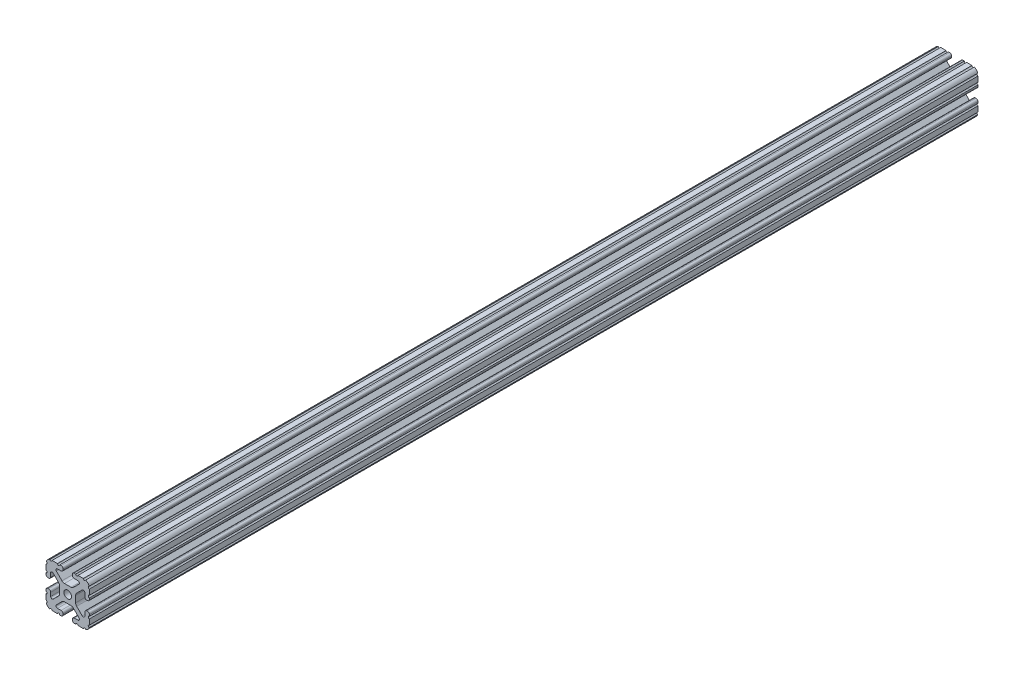
SolidWorks part; units mm, degrees
ref_plane "Front Plane" through (0, 0, 0) normal (0, 0, 1) x (1, 0, 0)
ref_plane "Top Plane" through (0, 0, 0) normal (0, 1, 0) x (1, 0, 0)
ref_plane "Right Plane" through (0, 0, 0) normal (1, 0, 0) x (0, 0, -1)
sketch "Sketch2" plane through (0, 0, 0) normal (0, 0, 1) x (1, 0, 0)
  line L0 (0, 19.05) -> (0, -19.05) construction
  line L1 (-19.05, 0) -> (19.05, 0) construction
  line L2 (4.064, -19.05) -> (19.05, -19.05)
  line L3 (19.05, -19.05) -> (19.05, -4.064)
  line L4 (4.064, -19.05) -> (4.064, -14.986)
  line L5 (4.064, -14.986) -> (12.1123, -14.986)
  line L6 (12.1123, -14.986) -> (4.1113, -6.985)
  line L7 (0, 0) -> (19.05, -19.05) construction
  line L8 (19.05, -4.064) -> (14.986, -4.064)
  line L9 (14.986, -4.064) -> (14.986, -12.1123)
  line L10 (14.986, -12.1123) -> (6.985, -4.1113)
  circle A0 centre (0, 0) radius 3.3274
  arc A1 (8.9963, -14.986) -> (9.909, -12.7826) centre (8.9963, -13.6953) ccw construction
  point P8 (0, -6.985)
  dimension "Center Hole Diameter" = 6.6548
  dimension "Rail Height" = 38.1
  dimension "Rail Width" = 38.1
  dimension "T-Slot Width" = 8.128
  dimension "Slot Inner Width" = 20.574
  dimension "Thickness" = 4.064
  dimension "Slot Depth" = 8.001
  dimension "D1" = 4.064
sketch "Sketch3" plane through (0, 0, 0) normal (1, 0, 0) x (0, 0, -1)
  line L0 (-390, -19.05) -> (390, -19.05) construction
  line L1 (-364.6, 0) -> (364.6, 0) construction
  dimension "Length" = 780
  dimension "D1" = 25.4
sketch "Sketch4" plane through (0, 0, 0) normal (0, 0, 1) x (1, 0, 0)
  line L0 (5.7912, -19.05) -> (14.3002, -19.05)
  line L1 (4.064, -19.05) -> (19.05, -19.05) construction
  line L2 (4.064, -19.05) -> (4.064, -14.986) construction
  line L3 (4.064, -14.986) -> (12.1123, -14.986) construction
  line L4 (4.064, -16.7132) -> (4.064, -17.3228)
  line L5 (5.7912, -14.986) -> (8.9963, -14.986)
  line L6 (0, -6.985) -> (2.833, -6.985)
  line L7 (12.1123, -14.986) -> (4.1113, -6.985) construction
  line L8 (5.0152, -7.8889) -> (9.909, -12.7826)
  line L9 (19.05, -19.05) -> (19.05, -4.064) construction
  line L10 (14.986, -12.1123) -> (6.985, -4.1113) construction
  line L11 (14.986, -4.064) -> (14.986, -12.1123) construction
  line L12 (14.986, -8.9963) -> (14.986, -5.7912)
  line L13 (19.05, -4.064) -> (14.986, -4.064) construction
  line L14 (16.7132, -4.064) -> (17.3228, -4.064)
  line L15 (19.05, -5.7912) -> (19.05, -14.3002)
  line L16 (12.7826, -9.909) -> (7.8889, -5.0152)
  line L17 (6.985, 0) -> (6.985, -2.833)
  line L18 (-19.05, 0) -> (19.05, 0) construction
  line L19 (0, -6.985) -> (0, -3.3274)
  line L20 (0, 19.05) -> (0, -19.05) construction
  line L21 (6.985, 0) -> (3.3274, 0)
  arc A0 (4.064, -17.3228) -> (5.7912, -19.05) centre (5.7912, -17.3228) ccw
  arc A2 (4.064, -16.7132) -> (5.7912, -14.986) centre (5.7912, -16.7132) cw
  arc A3 (8.9963, -14.986) -> (9.909, -12.7826) centre (8.9963, -13.6953) ccw
  arc A4 (2.833, -6.985) -> (5.0152, -7.8889) centre (2.833, -10.0711) cw
  arc A5 (14.3002, -19.05) -> (19.05, -14.3002) centre (14.3002, -14.3002) ccw
  arc A6 (12.7826, -9.909) -> (14.986, -8.9963) centre (13.6953, -8.9963) ccw
  arc A7 (14.986, -5.7912) -> (16.7132, -4.064) centre (16.7132, -5.7912) cw
  arc A8 (17.3228, -4.064) -> (19.05, -5.7912) centre (17.3228, -5.7912) cw
  arc A9 (7.8889, -5.0152) -> (6.985, -2.833) centre (10.0711, -2.833) cw
  circle A10 centre (0, 0) radius 3.3274 construction
  arc A11 (0, -3.3274) -> (3.3274, 0) centre (0, 0) ccw
  dimension "D1" = 4.7498
  dimension "D2" = 3.0861
  dimension "D3" = 1.7272
extrude "Boss-Extrude1" add sketch "Sketch4" along normal mid plane 780
sketch "Sketch5" plane through (0, 0, 0) normal (0, 0, 1) x (1, 0, 0)
  line L0 (4.064, -19.05) -> (19.05, -19.05) construction
  line L1 (5.7912, -14.986) -> (8.9963, -14.986) construction
  line L3 (0, 0) -> (19.05, -19.05) construction
  line L4 (8.9963, -14.986) -> (8.9963, -19.05) construction
  line L5 (12.1123, -14.986) -> (4.1113, -6.985) construction
  circle A0 centre (14.7395, -19.05) radius 1.016
  circle A1 centre (7.9803, -19.05) radius 1.016
  circle A2 centre (19.05, -14.7395) radius 1.016
  circle A3 centre (19.05, -7.9803) radius 1.016
  point P10 (7.3938, -14.986)
  point P12 (13.6953, -8.9963)
  dimension "D1" = 2.032
extrude "Cut-Extrude1" cut sketch "Sketch5" against normal through all both and the other way through all
mirror "Mirror1" about plane through (0, 0, 0) normal (1, 0, 0) of bodies 137 134
mirror "Mirror2" about plane through (0, 0, 0) normal (0, 1, 0) of bodies 135
equation "\"D1@Boss-Extrude1\"=\"Length@Sketch3\""
equation "\"D1@Sketch2\"=\"Thickness@Sketch2\""
equation "\"D2@Sketch4\"=\"Slot Inner Width@Sketch2\"*0.15"
equation "\"D1@Sketch4\"=\"D3@Sketch4\"*2.75"
equation "\"D3@Sketch4\"=\"Thickness@Sketch2\"*0.425"
equation "\"D1@Sketch5\"=\"Thickness@Sketch2\"*0.5"
